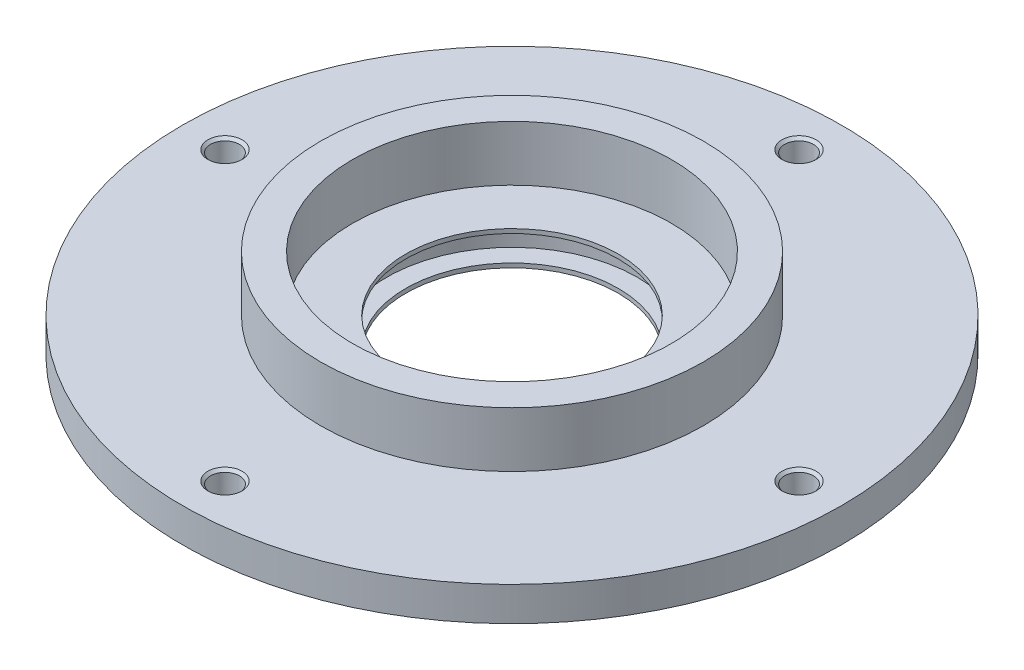
SolidWorks part; units mm, degrees
ref_plane "前视基准面" through (0, 0, 0) normal (0, 0, 1) x (1, 0, 0)
ref_plane "上视基准面" through (0, 0, 0) normal (0, 1, 0) x (1, 0, 0)
ref_plane "右视基准面" through (0, 0, 0) normal (1, 0, 0) x (0, 0, -1)
other "Configuration Table"
sketch "草图1" plane through (0, 0, 0) normal (0, 0, 1) x (1, 0, 0)
  line L0 (0, 34.8163) -> (0, -25.9388) construction
  line L1 (0, 0) -> (77.5, 0)
  line L2 (77.5, 0) -> (77.5, 8)
  line L3 (77.5, 8) -> (45, 8)
  line L4 (45, 8) -> (45, 21)
  line L5 (45, 21) -> (37.5, 21)
  line L6 (37.5, 21) -> (37.5, 8)
  line L7 (37.5, 8) -> (0, 8)
  line L8 (0, 8) -> (0, 0)
  dimension "D1" = 77.5
  dimension "D2" = 8
  dimension "D3" = 7.5
  dimension "D4" = 37.5
  dimension "D5" = 13
revolve "旋转1" add sketch "草图1" angle 360 about L8
sketch "草图2" plane through (0, 0, 0) normal (0, 1, 0) x (1, 0, 0)
  circle A0 centre (0, 0) radius 67.5
  circle A1 centre (67.5, 0) radius 4.5
  circle A2 centre (0, -67.5) radius 4.5
  circle A3 centre (-67.5, 0) radius 4.5
  circle A4 centre (0, 67.5) radius 4.5
  point P14 (0, 0)
  dimension "D1" = 4
  dimension "D2" = 135
hole_wizard "M8 螺纹孔1" positions "草图7" profile "草图8" tap size "M8" standard "GB" end condition through all
sketch "草图7" plane through (0, 8, 0) normal (0, 1, 0) x (1, 0, 0)
  point P0 (-67.5, 0)
  point P3 (67.5, 0)
  point P6 (0, -67.5)
  point P9 (0, 67.5)
sketch "草图8" plane through (-67.5, 8, 0) normal (1, 0, 0) x (0, 0, 1)
  line L0 (0, 0) -> (0, 8)
  line L1 (0, 8) -> (3.4, 8)
  line L2 (3.4, 8) -> (3.4, 0.625)
  line L3 (3.4, 0.625) -> (4.025, 0)
  line L5 (4.025, 0) -> (0, 0)
  line L6 (-3.4, 0.625) -> (-4.025, 0) construction
  line L11 (0, -6.35) -> (0, 107.95) construction
  dimension "通孔螺纹孔钻头直径" = 6.8
  dimension "通孔螺纹孔钻头深度" = 8
  dimension "近端锥形沉头孔直径" = 8.05
  dimension "近端锥形沉头孔角度" = 90
cosmetic thread "孔螺蚊线1" parameters "D2"=8
cosmetic thread "孔螺蚊线2" parameters "D2"=8
cosmetic thread "孔螺蚊线3" parameters "D2"=8
cosmetic thread "孔螺蚊线4" parameters "D2"=8
sketch "草图3" plane through (0, 0, 0) normal (0, 1, 0) x (1, 0, 0)
  circle A0 centre (0, 0) radius 25
  dimension "D1" = 50
extrude "切除-拉伸3" cut sketch "草图3" along normal blind 21
sketch "草图4" plane through (0, 0, 0) normal (1, 0, 0) x (0, 0, -1)
  line L0 (0, 0) -> (0, 4)
  line L1 (0, 4) -> (14.5, 4)
  line L2 (29.5, 4) -> (29.5, 1)
  line L3 (29.5, 1) -> (25, 1)
  line L5 (25, 7) -> (29.5, 7)
  line L6 (29.5, 7) -> (29.5, 4)
  line L7 (0, 0) -> (0, 13.0193) construction
  line L8 (25, 7) -> (14.5, 7)
  line L9 (0, 7) -> (0, 1)
  line L10 (14.5, 7) -> (14.5, 1)
  line L11 (14.5, 1) -> (25, 1)
  dimension "D1" = 15
  dimension "D2" = 14.5
  dimension "D3" = 6
revolve "切除-旋转2" cut sketch "草图4" angle 360 about L7
